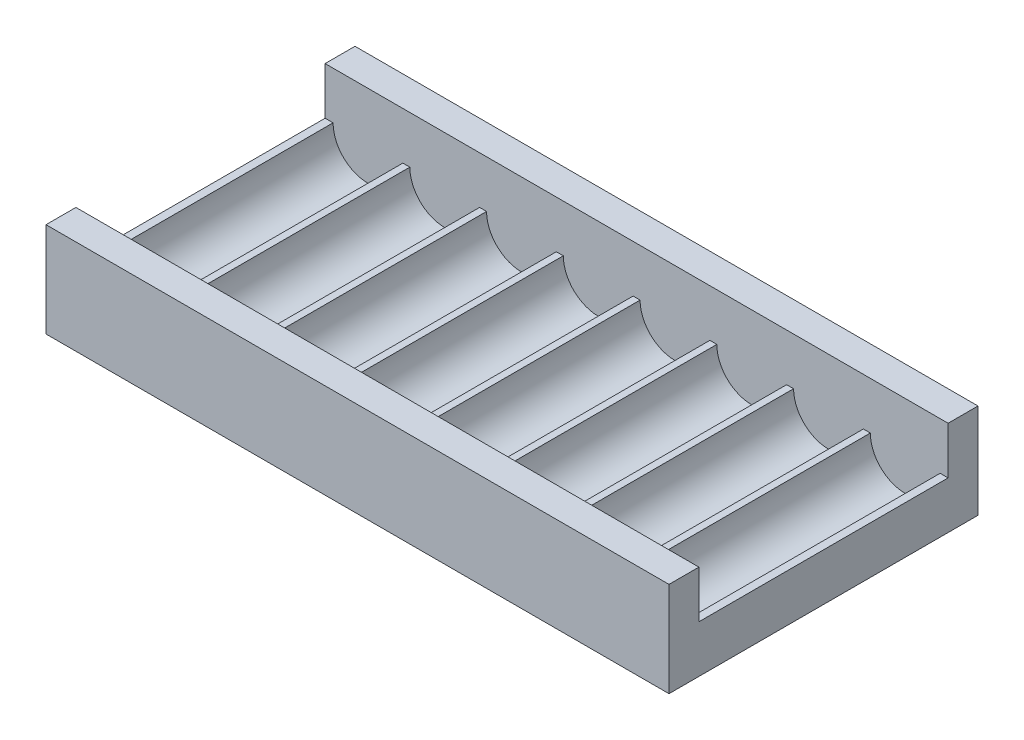
SolidWorks part; units mm, degrees
ref_plane "前视基准面" through (0, 0, 0) normal (0, 0, 1) x (1, 0, 0)
ref_plane "上视基准面" through (0, 0, 0) normal (0, 1, 0) x (1, 0, 0)
ref_plane "右视基准面" through (0, 0, 0) normal (1, 0, 0) x (0, 0, -1)
sketch "草图1" plane through (0, 0, 0) normal (0, 0, 1) x (1, 0, 0)
  line L1 (62.5, 9.5) -> (-62.5, 9.5)
  line L2 (62.5, 9.5) -> (62.5, -9.5)
  line L3 (62.5, -9.5) -> (-62.5, -9.5)
  line L4 (-62.5, 9.5) -> (-62.5, -9.5)
  line L5 (62.5, 9.5) -> (-62.5, -9.5) construction
  line L6 (62.5, -9.5) -> (-62.5, 9.5) construction
  point P0 (0, 0)
  point P5 (0, 0)
  point P6 (0, 0)
  point P8 (0, 0)
  point P9 (0, 0)
  point P10 (0, 0)
  point P12 (-60.9217, -8.9436)
  dimension "D1" = 125
  dimension "D2" = 19
extrude "凸台-拉伸1" add sketch "草图1" along normal blind 6
ref_plane "基准面1" through (0, 0, 6) normal (0, 0, 1) x (1, 0, 0)
sketch "草图2" plane through (0, 0, 6) normal (0, 0, 1) x (1, 0, 0)
  line L0 (-62.5, 0) -> (-60.9, 0)
  line L1 (-62.5, 9.5) -> (-62.5, -9.5) construction
  line L2 (62.5, -9.5) -> (62.5, 9.5) construction
  line L3 (-62.5, 0) -> (-62.5, -9.5)
  line L4 (-62.5, -9.5) -> (62.5, -9.5)
  line L5 (62.5, 0) -> (62.5, -9.5)
  line L6 (-46.9, 0) -> (-45.5, 0)
  line L7 (-31.5, 0) -> (-30.1, 0)
  line L8 (-16.1, 0) -> (-14.7, 0)
  line L9 (-0.7, 0) -> (0.7, 0)
  line L10 (14.7, 0) -> (16.1, 0)
  line L11 (30.1, 0) -> (31.5, 0)
  line L12 (45.5, 0) -> (46.9, 0)
  line L13 (60.9, 0) -> (62.5, 0)
  arc A0 (-60.9, 0) -> (-46.9, 0) centre (-53.9, 0) ccw
  arc A1 (-45.5, 0) -> (-31.5, 0) centre (-38.5, 0) ccw
  arc A2 (-30.1, 0) -> (-16.1, 0) centre (-23.1, 0) ccw
  arc A3 (-14.7, 0) -> (-0.7, 0) centre (-7.7, 0) ccw
  arc A4 (0.7, 0) -> (14.7, 0) centre (7.7, 0) ccw
  arc A5 (16.1, 0) -> (30.1, 0) centre (23.1, 0) ccw
  arc A6 (31.5, 0) -> (45.5, 0) centre (38.5, 0) ccw
  arc A7 (46.9, 0) -> (60.9, 0) centre (53.9, 0) ccw
  dimension "D1" = 8.6
  dimension "D2" = 14
  dimension "D4" = 14
  dimension "D6" = 14
  dimension "D8" = 14
  dimension "D10" = 14
  dimension "D12" = 14
  dimension "D14" = 14
  dimension "D16" = 14
  dimension "D3" = 15.4
  dimension "D5" = 15.4
  dimension "D7" = 15.4
  dimension "D9" = 15.4
  dimension "D11" = 15.4
  dimension "D13" = 15.4
  dimension "D15" = 15.4
extrude "凸台-拉伸2" add sketch "草图2" along normal blind 50
ref_plane "基准面2" through (0, 0, 56) normal (0, 0, 1) x (1, 0, 0)
sketch "草图3" plane through (0, 0, 56) normal (0, 0, 1) x (1, 0, 0)
  line L1 (-62.5, -9.5) -> (62.5, -9.5)
  line L2 (-62.5, -9.5) -> (-62.5, 9.5)
  line L3 (-62.5, 9.5) -> (62.5, 9.5)
  line L4 (62.5, -9.5) -> (62.5, 9.5)
extrude "凸台-拉伸3" add sketch "草图3" along normal blind 6
ref_plane "基准面4" through (0, 9.5, 0) normal (0, 1, 0) x (1, 0, 0)
